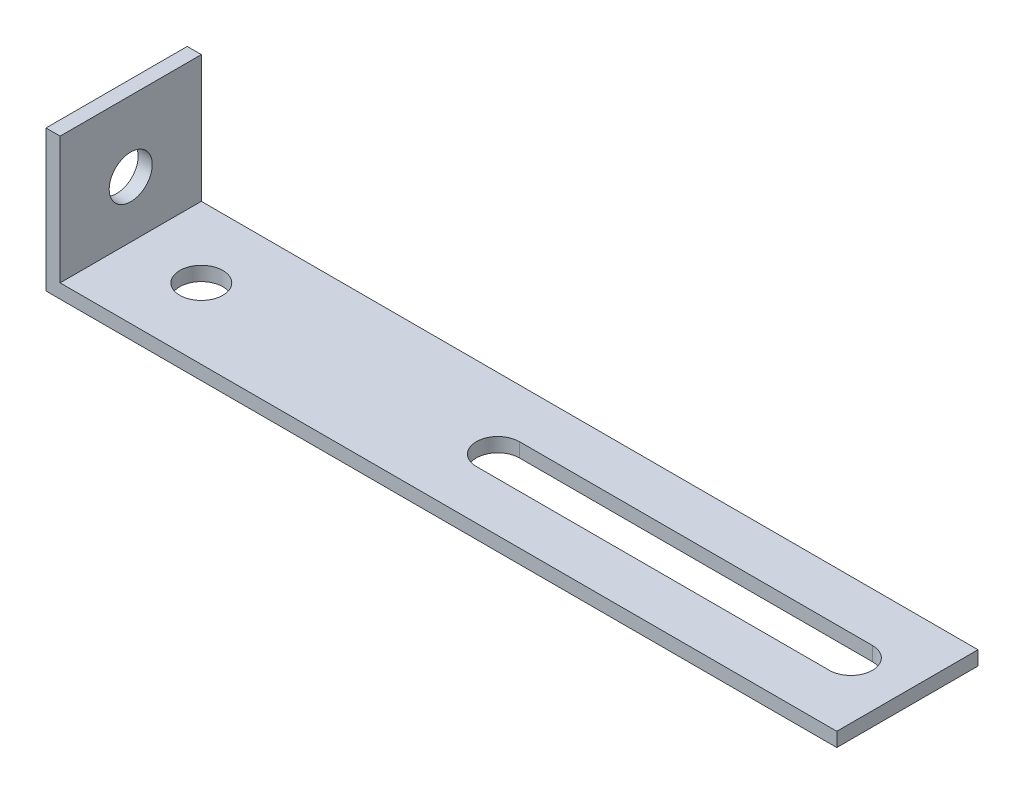
SolidWorks part; units mm, degrees
ref_plane "Front" through (0, 0, 0) normal (0, 0, 1) x (1, 0, 0)
ref_plane "Top" through (0, 0, 0) normal (0, 1, 0) x (1, 0, 0)
ref_plane "Right" through (0, 0, 0) normal (1, 0, 0) x (0, 0, -1)
sketch "Sketch1" plane through (0, 0, 0) normal (0, 0, 1) x (1, 0, 0)
  line L0 (0, 0) -> (0, 20)
  line L1 (0, 20) -> (2, 20)
  line L2 (2, 20) -> (2, 2)
  line L3 (2, 2) -> (112, 2)
  line L4 (112, 2) -> (112, 0)
  line L5 (112, 0) -> (0, 0)
  dimension "D1" = 2
  dimension "D2" = 20
  dimension "D3" = 110
  dimension "D4" = 18
extrude "Boss-Extrude1" add sketch "Sketch1" along normal blind 20
sketch "Sketch2" plane through (0, 0, 0) normal (-1, 0, 0) x (0, 0, 1)
  line L0 (20, 20) -> (0, 20) construction
  line L1 (0, 20) -> (0, 0) construction
  circle A0 centre (10, 10) radius 3.05
  dimension "D1" = 6.1
  dimension "D2" = 10
  dimension "D3" = 10
extrude "Cut-Extrude1" cut sketch "Sketch2" against normal through all contours A0
sketch "Sketch3" plane through (0, 2, 0) normal (0, 1, 0) x (1, 0, 0)
  line L0 (2, -20) -> (2, 0) construction
  line L2 (112, 0) -> (2, 0) construction
  line L3 (54, -13.05) -> (104, -13.05)
  line L4 (54, -6.95) -> (104, -6.95)
  line L5 (112, -20) -> (112, 0) construction
  circle A0 centre (12, -10) radius 3.05
  arc A1 (54, -6.95) -> (54, -13.05) centre (54, -10) ccw
  arc A2 (104, -13.05) -> (104, -6.95) centre (104, -10) ccw
  point P11 (2, -10)
  dimension "D1" = 6.1
  dimension "D2" = 8
  dimension "D4" = 3.05
  dimension "D3" = 10
  dimension "D5" = 42
  dimension "D6" = 10
extrude "Cut-Extrude2" cut sketch "Sketch3" against normal through all
